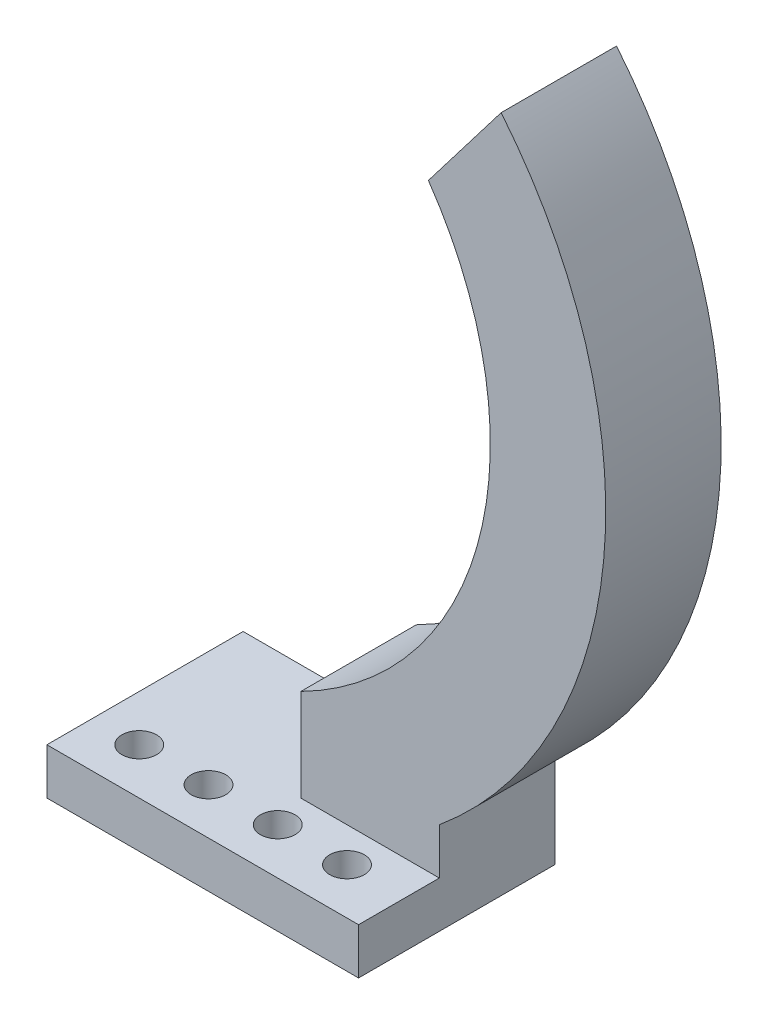
SolidWorks part; units mm, degrees
ref_plane "Front Plane" through (0, 0, 0) normal (0, 0, 1) x (1, 0, 0)
ref_plane "Top Plane" through (0, 0, 0) normal (0, 1, 0) x (1, 0, 0)
ref_plane "Right Plane" through (0, 0, 0) normal (1, 0, 0) x (0, 0, -1)
sketch "Sketch1" plane through (0, 0, 0) normal (0, 0, 1) x (1, 0, 0)
  line L28 (-5.354, 64.1029) -> (0.9478, 55.8676)
  line L31 (12, 12) -> (12, 4)
  line L32 (0, 0) -> (27, 0)
  line L35 (27, 0) -> (27, 4)
  line L39 (0, 8) -> (0, 4)
  line L43 (0, 0) -> (0, 4)
  line L44 (12, 4) -> (27, 4)
  arc A4 (0.9478, 55.8676) -> (12, 12) centre (25.5839, 38.7484) ccw
  arc A5 (-5.354, 64.1029) -> (0, 8) centre (25.5839, 38.7484) ccw
  dimension "D3" = 8
  dimension "D4" = 12
  dimension "D5" = 30
  dimension "D1" = 40
  dimension "D6" = 27
  dimension "D7" = 4
extrude "Boss-Extrude1" add sketch "Sketch1" along normal blind 10
sketch "Sketch3" plane through (0, 0, 0) normal (0, 0, 1) x (1, 0, 0)
  line L0 (0, 4) -> (27, 4)
  line L2 (0, 0) -> (0, 4)
  line L5 (27, 4) -> (27, 0)
  line L6 (27, 0) -> (0, 0)
  dimension "D1" = 27
extrude "Boss-Extrude2" add sketch "Sketch3" along normal blind 17 contours L6 L2 L0 L5
ref_plane "Plane1" through (0, 4, 0) normal (0, 1, 0) x (1, 0, 0)
sketch "Sketch4" plane through (0, 4, 0) normal (0, 1, 0) x (1, 0, 0)
  line L0 (27, -17) -> (0, -17) construction
  line L5 (27, -17) -> (27, 0) construction
  circle A0 centre (5, -13) radius 1.5
  circle A1 centre (11, -13) radius 1.5
  circle A2 centre (17, -13) radius 1.5
  circle A3 centre (23, -13) radius 1.5
  dimension "D1" = 6
  dimension "D2" = 6
  dimension "D3" = 6
  dimension "D4" = 4
  dimension "D5" = 4
extrude "Cut-Extrude1" cut sketch "Sketch4" against normal blind 4 contours A0 | A1 | A2 | A3
mirror "Mirror8" about plane through (27, 0, 10) normal (-1, 0, 0) of "Cut-Extrude1", "Boss-Extrude1", "Boss-Extrude2"
ref_plane "Plane3" through (0, 0, 0) normal (-1, 0, 0) x (0, 0, 1)
sketch "Sketch5" plane through (0, 0, 0) normal (-1, 0, 0) x (0, 0, 1)
  line L1 (-3.9007, 66.8549) -> (20.9007, 66.8549)
  line L2 (-3.9007, 66.8549) -> (-3.9007, -3.2951)
  line L3 (-3.9007, -3.2951) -> (20.9007, -3.2951)
  line L4 (20.9007, 66.8549) -> (20.9007, -3.2951)
extrude "Cut-Extrude2" cut sketch "Sketch5" against normal blind 27 and the other way blind 15
